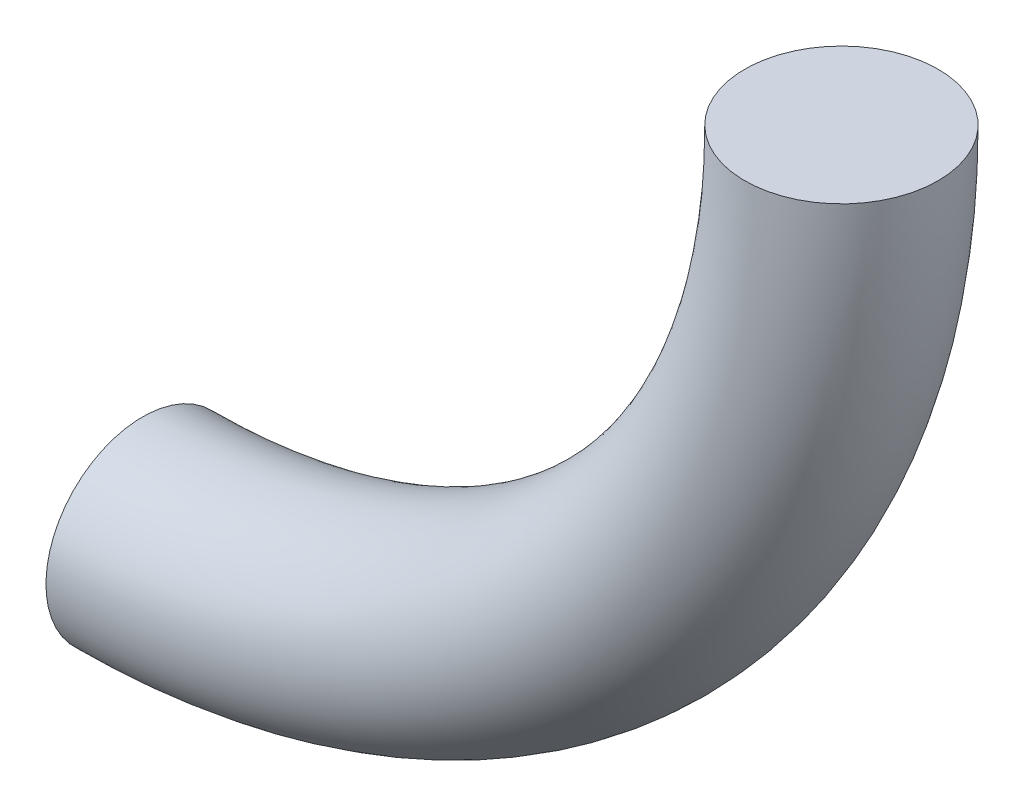
SolidWorks part; units mm, degrees
ref_plane "Front Plane" through (0, 0, 0) normal (0, 0, 1) x (1, 0, 0)
ref_plane "Top Plane" through (0, 0, 0) normal (0, 1, 0) x (1, 0, 0)
ref_plane "Right Plane" through (0, 0, 0) normal (1, 0, 0) x (0, 0, -1)
sketch "SweepSection" plane through (0, 0, 0) normal (1, 0, 0) x (0, 0, -1)
  circle A0 centre (0, 0) radius 5.713
  dimension "D1" = 11.426
sketch "SweepPath" plane through (0, 0, 0) normal (0, 0, 1) x (1, 0, 0)
  arc A0 (0, 0) -> (41.297, 41.297) centre (0, 41.297) ccw
  dimension "D1" = 41.297
sweep "OrdinarySweptBoss" add profiles "SweepSection" path "SweepPath"
